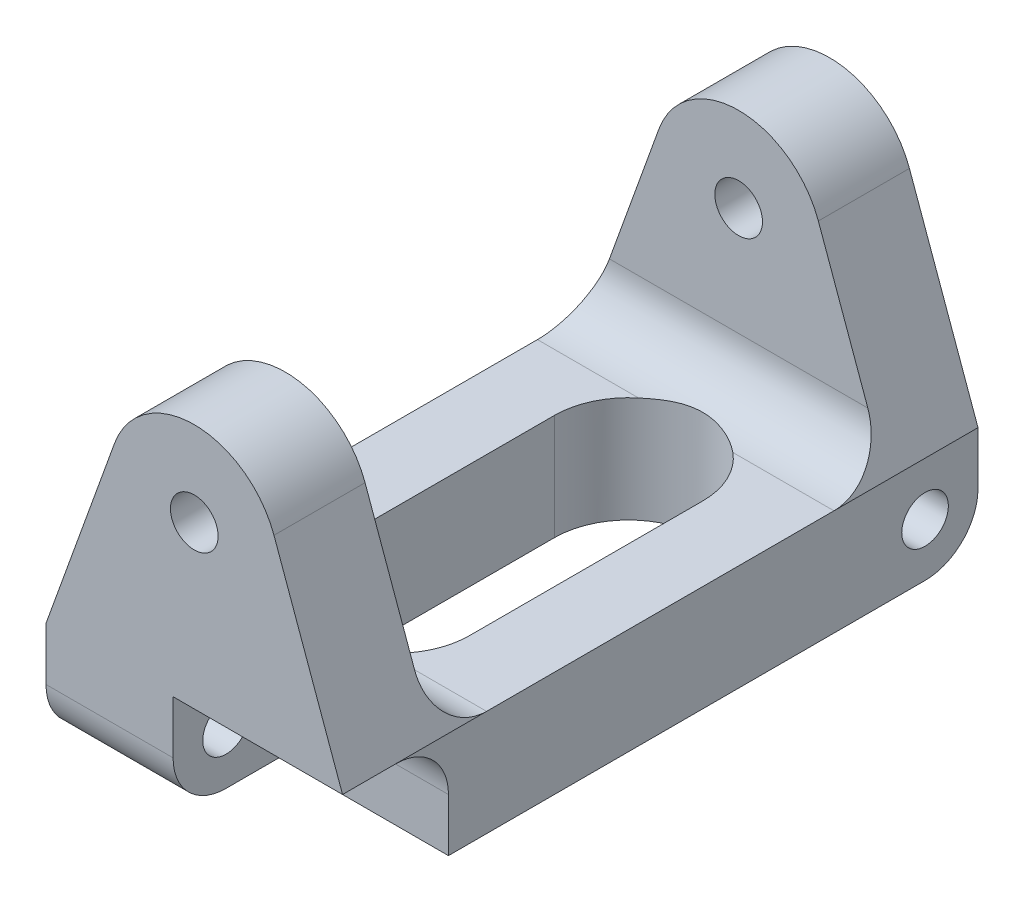
SolidWorks part; units mm, degrees
ref_plane "Front Plane" through (0, 0, 0) normal (0, 0, 1) x (1, 0, 0)
ref_plane "Top Plane" through (0, 0, 0) normal (0, 1, 0) x (1, 0, 0)
ref_plane "Right Plane" through (0, 0, 0) normal (1, 0, 0) x (0, 0, -1)
sketch "Sketch1" plane through (0, 0, 0) normal (0, 1, 0) x (1, 0, 0)
  line L0 (-7, 0) -> (7, 0)
  line L1 (-7, -15) -> (7, -15)
  line L2 (-7, -15) -> (-7, 15)
  line L3 (-7, 15) -> (7, 15)
  line L4 (7, -15) -> (7, 15)
  line L5 (-7, -15) -> (7, 15) construction
  line L6 (-7, 15) -> (7, -15) construction
  point P0 (0, 0)
  dimension "D1" = 30
  dimension "D2" = 14
extrude "Boss-Extrude1" add sketch "Sketch1" against normal blind 5 contours L0 L4 L3 L2
sketch "Sketch3" plane through (-7, 0, 0) normal (-1, 0, 0) x (0, 0, 1)
  line L0 (-15, -2.5) -> (-12.5, -2.5) construction
  line L1 (-15, -5) -> (-15, 0) construction
  circle A0 centre (-12.5, -2.5) radius 1.1
  dimension "D1" = 2.2
  dimension "D2" = 2.5
extrude "Cut-Extrude1" cut sketch "Sketch3" against normal up to surface (14 mm away) up to face at (7, -2.5, -7.5)
ref_plane "Plane1" through (0, 0, -10.7) normal (0, 0, 1) x (1, 0, 0)
sketch "Sketch4" plane through (0, 0, -15) normal (0, 0, -1) x (-1, 0, 0)
  line L0 (0, 0) -> (0, 7.625) construction
  line L1 (7, 0) -> (-7, 0) construction
  line L2 (-7, 0) -> (-3.7631, 8.9812)
  line L3 (7, 0) -> (3.7631, 8.9812)
  line L4 (7, 0) -> (-7, 0)
  line L5 (7, -5) -> (-7, -5) construction
  arc A0 (3.7631, 8.9812) -> (-3.7631, 8.9812) centre (0, 7.625) ccw
  dimension "D2" = 8
  dimension "D1" = 12.625
extrude "Boss-Extrude2" add sketch "Sketch4" against normal up to surface (4.3 mm away) up to plane "Plane1"
sketch "Sketch5" plane through (0, 0, -15) normal (0, 0, -1) x (-1, 0, 0)
  circle A0 centre (0, 7.625) radius 1.125
  arc A1 (3.7631, 8.9812) -> (-3.7631, 8.9812) centre (0, 7.625) ccw construction
  dimension "D1" = 2.25
extrude "Cut-Extrude2" cut sketch "Sketch5" against normal up to surface (4.3 mm away) up to face at (0, 5.1516, -10.7)
fillet "Fillet1" radius 2.5 2 edges at (0, -5, -15) (0, 0, -10.7)
sketch "Sketch6" plane through (0, 0, 0) normal (0, 1, 0) x (1, 0, 0)
  line L0 (0, -5.5) -> (0, 5.5) construction
  line L1 (-3.5, -5.5) -> (-3.5, 5.5)
  line L2 (3.5, -5.5) -> (3.5, 5.5)
  arc A0 (-3.5, -5.5) -> (3.5, -5.5) centre (0, -5.5) ccw
  arc A1 (3.5, 5.5) -> (-3.5, 5.5) centre (0, 5.5) ccw
  point P2 (0, 0)
  dimension "D2" = 3.5
  dimension "D1" = 11
extrude "Cut-Extrude3" cut sketch "Sketch6" against normal up to surface (5 mm away) and the other way up to surface up to face at (0, -5, -6.25) other way up to face at (0, 0.9911, -9.7089)
mirror "Mirror1" about plane through (0, 0, 0) normal (0, 0, 1) of bodies 105
sketch "Sketch8" plane through (7, 0, 0) normal (1, 0, 0) x (0, 0, -1)
  circle A1 centre (-12.5, -2.5) radius 1.1 construction
  circle A2 centre (-12.5, -2.5) radius 1.1
sketch "Sketch10" plane through (-7, 0, 0) normal (-1, 0, 0) x (0, 0, 1)
  line L0 (12.5, 0) -> (15, 0)
  line L1 (15, 0) -> (15, -2.5)
  line L2 (10, -2.5) -> (10, -5)
  line L3 (12.5, -5) -> (-12.5, -5) construction
  line L4 (10, -5) -> (12.5, -5)
  circle A0 centre (12.5, -2.5) radius 2.5
  arc A1 (12.5, -5) -> (15, -2.5) centre (12.5, -2.5) ccw construction
  line M4 (-12.5, -5) -> (12.5, -5)
  arc M5 (12.5, -5) -> (15, -2.5) centre (12.5, -2.5) ccw
  line M6 (15, -2.5) -> (15, 0)
  line M7 (15, 0) -> (8.2, 0)
extrude "Cut-Extrude4" cut sketch "Sketch10" along normal blind 8 from surface at -14 contours A0 M5 | A0 M6 M7 | A0 L2 M4 starting at face at (7, -2.5, -13.6)
